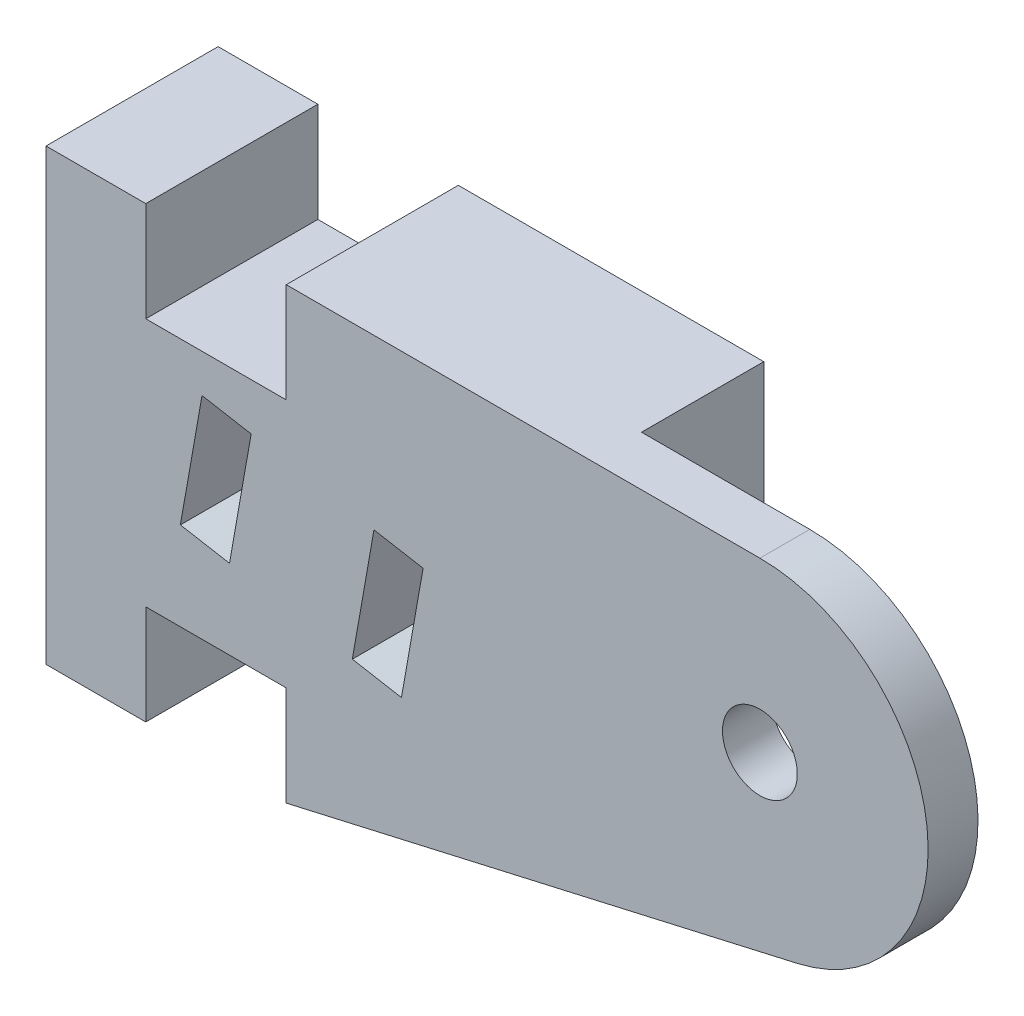
SolidWorks part; units mm, degrees
ref_plane "Front Plane" through (0, 0, 0) normal (0, 0, 1) x (1, 0, 0)
ref_plane "Top Plane" through (0, 0, 0) normal (0, 1, 0) x (1, 0, 0)
ref_plane "Right Plane" through (0, 0, 0) normal (1, 0, 0) x (0, 0, -1)
sketch "Sketch1" plane through (0, 0, 0) normal (0, 0, 1) x (1, 0, 0)
  line L0 (0, 0) -> (0, 18.0003)
  line L1 (9.6315, 0) -> (9.6315, 4)
  line L2 (9.6315, 4) -> (4, 4)
  line L4 (9.6315, 18.0003) -> (9.6315, 14.0003)
  line L5 (9.6315, 14.0003) -> (4, 14.0003)
  line L6 (0, 0) -> (4, 0)
  line L7 (4, 0) -> (4, 4)
  line L12 (4, 18.0003) -> (4, 14.0003)
  line L13 (0, 18.0003) -> (4, 18.0003)
  line L19 (9.6315, 0) -> (30.1232, 4.6795)
  line L21 (9.6315, 18.0003) -> (28.6215, 18.0003)
  line L22 (14.2505, 5.9748) -> (15.1187, 10.8988)
  line L23 (13.1491, 11.2461) -> (15.1187, 10.8988)
  line L24 (12.2808, 6.3221) -> (13.1491, 11.2461)
  line L25 (14.2505, 5.9748) -> (12.2808, 6.3221)
  line L26 (6.2554, 12.4616) -> (8.225, 12.1143)
  line L27 (7.3568, 7.1903) -> (8.225, 12.1143)
  line L28 (7.3568, 7.1903) -> (5.3872, 7.5376)
  line L29 (5.3872, 7.5376) -> (6.2554, 12.4616)
  circle A2 centre (28.6215, 11.2553) radius 12.12 construction
  circle A3 centre (28.6215, 11.2553) radius 1.5
  arc A4 (28.6215, 18.0003) -> (30.1232, 4.6795) centre (28.6215, 11.2553) cw
  dimension "D16" = 4.6795
  dimension "D15" = 20.4917
  dimension "D17" = 18.99
  dimension "D2" = 7.5376
  dimension "D10" = 6.745
  dimension "D11" = 3
  dimension "D14" = 24.24
  dimension "D3" = 7.1903
  dimension "D4" = 12.4616
  dimension "D5" = 12.1143
  dimension "D6" = 5.3872
  dimension "D7" = 7.3568
  dimension "D8" = 18.0003
  dimension "D9" = 5.6315
  dimension "D13" = 9.6315
extrude "Boss-Extrude1" add sketch "Sketch1" along normal blind 6.9
sketch "Sketch4" plane through (0, 0, 0) normal (0, 0, 1) x (1, 0, 0)
  line L6 (21.8765, 2.7963) -> (30.1232, 4.6795)
  line L7 (21.8765, 18.0003) -> (28.6215, 18.0003)
  line L8 (21.8765, 18.0003) -> (21.8765, 2.7963)
  arc A1 (28.6215, 18.0003) -> (30.1232, 4.6795) centre (28.6215, 11.2553) cw
  dimension "D1" = 21.8765
extrude "Cut-Extrude2" cut sketch "Sketch4" along normal blind 4.9
sketch "Sketch5" plane through (0, 0, 0) normal (-1, 0, 0) x (0, 0, 1)
  circle A0 centre (2.45, 10.0003) radius 1
  dimension "D1" = 2
  dimension "D3" = 10.0003
  dimension "D2" = 2.45
extrude "Cut-Extrude3" cut sketch "Sketch5" against normal blind 7
sketch "Sketch6" plane through (5.9053, -1.0413, 0) normal (-0.9848, 0.1736, 0) x (0, 0, 1)
  circle A1 centre (2.45, 10.8586) radius 1
  dimension "D1" = 2
  dimension "D3" = 2.45
  dimension "D2" = 10.8586
extrude "Cut-Extrude4" cut sketch "Sketch6" against normal up to surface and the other way up to surface (2 mm away) up to face at (21.8765, 10.3983, 2.45) other way up to face at (5.6451, 9.0003, 2.45)
equation "\"D17@Sketch1\"= \"HB@parametersSketch@prostheticParameters.SLDPRT\" * 0.211"
